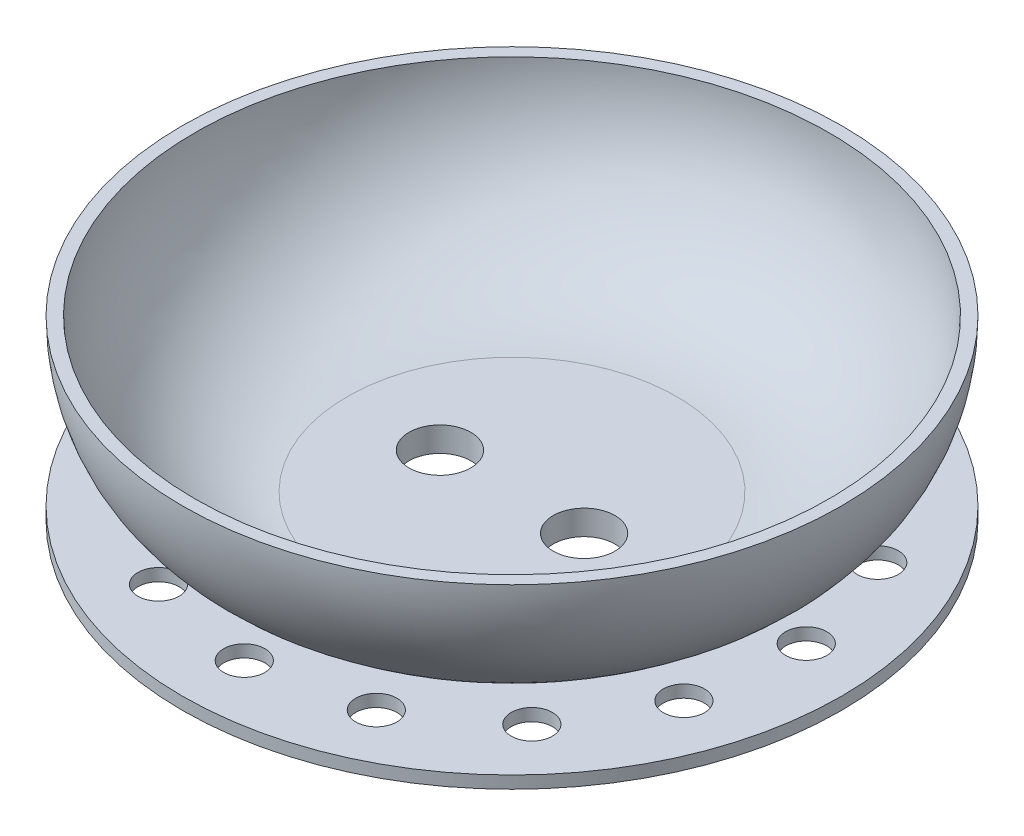
SolidWorks part; units mm, degrees
ref_plane "Front" through (0, 0, 0) normal (0, 0, 1) x (1, 0, 0)
ref_plane "Top" through (0, 0, 0) normal (0, 1, 0) x (1, 0, 0)
ref_plane "Right" through (0, 0, 0) normal (1, 0, 0) x (0, 0, -1)
sketch "Sketch1" plane through (0, 0, 0) normal (0, 0, 1) x (1, 0, 0)
  line L0 (0, 25.4) -> (0, 0) construction
  line L1 (-101.6, 0) -> (101.6, 0) construction
  line L2 (-101.6, 0) -> (-101.6, 25.4) construction
  line L3 (-101.6, 25.4) -> (101.6, 25.4) construction
  line L4 (101.6, 0) -> (101.6, 25.4) construction
  line L5 (0, 0) -> (50.8, 0)
  line L7 (0, 3.81) -> (50.8, 3.81)
  line L9 (97.79, 50.8) -> (101.6, 50.8)
  line L11 (0, 3.81) -> (0, 0)
  line L12 (94.3936, 68.3402) -> (115.2887, 37.2755) construction
  line L13 (101.6, 50.8) -> (112.1273, 35.149) construction
  arc A0 (50.8, 0) -> (101.6, 50.8) centre (50.8, 50.8) ccw
  arc A1 (50.8, 3.81) -> (97.79, 50.8) centre (50.8, 50.8) ccw
  arc A3 (50.8, 3.81) -> (94.3936, 68.3402) centre (50.8, 50.8) ccw construction
  dimension "D1" = 203.2
  dimension "D2" = 25.4
  dimension "D3" = 50.8
  dimension "D4" = 3.81
  dimension "D6" = 3.81
revolve "Revolve1" add sketch "Sketch1" angle 360 about L0
sketch "Sketch2" plane through (0, 0, 0) normal (0, -1, 0) x (1, 0, 0)
  circle A0 centre (0, 0) radius 101.6
  dimension "D1" = 203.2
extrude "Boss-Extrude1" add sketch "Sketch2" along normal blind 3.81
sketch "Sketch3" plane through (0, -3.81, 0) normal (0, -1, 0) x (1, 0, 0)
  line L0 (0, 0) -> (0, 82.55) construction
  circle A0 centre (0, 82.55) radius 6.35
  dimension "D1" = 12.7
  dimension "D2" = 82.55
extrude "Cut-Extrude1" cut sketch "Sketch3" against normal up to surface (3.81 mm away) up to face at (0, 0, 50.8)
pattern_circular "CirPattern1" count 15 over 360 about axis through (0, 0, 0) along (0, 1, 0) of "Cut-Extrude1"
sketch "Sketch5" plane through (0, 3.81, 0) normal (0, 1, 0) x (1, 0, 0)
  line L0 (-22.225, 0) -> (22.225, 0) construction
  circle A0 centre (22.225, 0) radius 9.525
  circle A1 centre (-22.225, 0) radius 9.525
  dimension "D1" = 19.05
  dimension "D2" = 44.45
extrude "Cut-Extrude3" cut sketch "Sketch5" against normal through all
